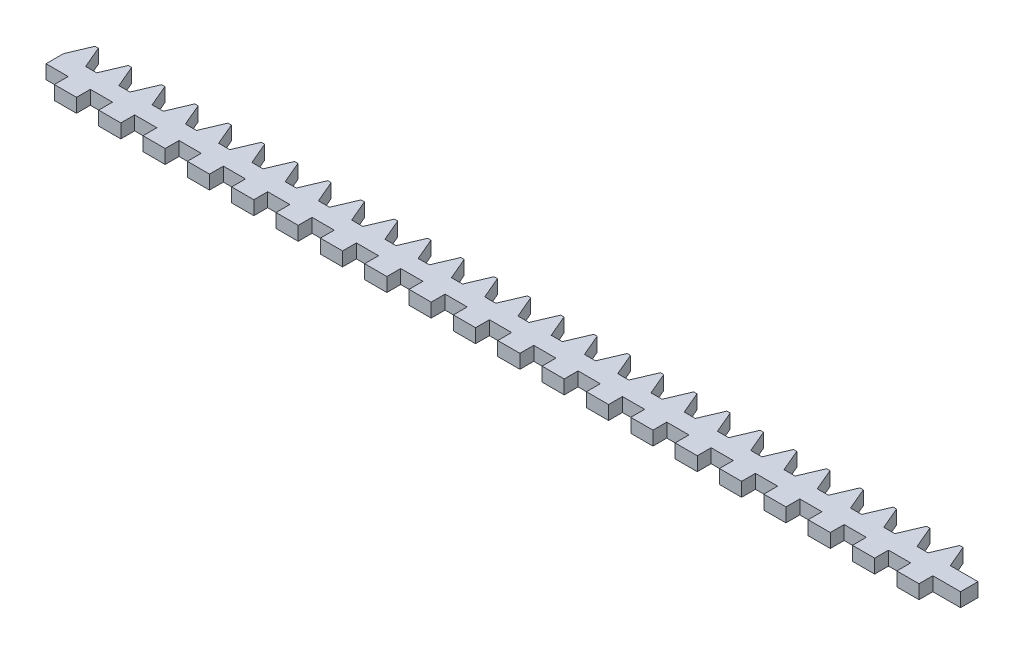
SolidWorks part; units mm, degrees
ref_plane "Front Plane" through (0, 0, 0) normal (0, 0, 1) x (1, 0, 0)
ref_plane "Top Plane" through (0, 0, 0) normal (0, 1, 0) x (1, 0, 0)
ref_plane "Right Plane" through (0, 0, 0) normal (1, 0, 0) x (0, 0, -1)
sketch "Sketch1" plane through (0, 0, 0) normal (0, 1, 0) x (1, 0, 0)
  line L0 (-139.4305, 2.0533) -> (-134.3505, 2.0533)
  line L1 (-134.3505, 6.0533) -> (-131.8105, 6.0533)
  line L2 (-139.4305, 6.0533) -> (-139.4305, 2.0533)
  line L3 (-134.3505, -1.1217) -> (-129.2705, -1.1217)
  line L4 (70.1195, 6.0533) -> (70.1195, 2.0533)
  line L5 (-129.2705, 2.0533) -> (-129.2705, -1.1217)
  line L6 (-134.3505, 2.0533) -> (-134.3505, -1.1217)
  line L7 (-129.2705, 2.0533) -> (-124.1905, 2.0533)
  line L8 (-124.1905, -1.1217) -> (-119.1105, -1.1217)
  line L9 (-119.1105, 2.0533) -> (-119.1105, -1.1217)
  line L10 (-124.1905, 2.0533) -> (-124.1905, -1.1217)
  line L11 (-119.1105, 2.0533) -> (-114.0305, 2.0533)
  line L12 (-114.0305, -1.1217) -> (-108.9505, -1.1217)
  line L13 (-108.9505, 2.0533) -> (-108.9505, -1.1217)
  line L14 (-114.0305, 2.0533) -> (-114.0305, -1.1217)
  line L15 (-108.9505, 2.0533) -> (-103.8705, 2.0533)
  line L16 (-103.8705, -1.1217) -> (-98.7905, -1.1217)
  line L17 (-98.7905, 2.0533) -> (-98.7905, -1.1217)
  line L18 (-103.8705, 2.0533) -> (-103.8705, -1.1217)
  line L19 (-98.7905, 2.0533) -> (-93.7105, 2.0533)
  line L20 (-93.7105, -1.1217) -> (-88.6305, -1.1217)
  line L21 (-88.6305, 2.0533) -> (-88.6305, -1.1217)
  line L22 (-93.7105, 2.0533) -> (-93.7105, -1.1217)
  line L23 (-88.6305, 2.0533) -> (-83.5505, 2.0533)
  line L24 (-83.5505, -1.1217) -> (-78.4705, -1.1217)
  line L25 (-78.4705, 2.0533) -> (-78.4705, -1.1217)
  line L26 (-83.5505, 2.0533) -> (-83.5505, -1.1217)
  line L27 (-78.4705, 2.0533) -> (-73.3905, 2.0533)
  line L28 (-73.3905, -1.1217) -> (-68.3105, -1.1217)
  line L29 (-68.3105, 2.0533) -> (-68.3105, -1.1217)
  line L30 (-73.3905, 2.0533) -> (-73.3905, -1.1217)
  line L31 (-68.3105, 2.0533) -> (-63.2305, 2.0533)
  line L32 (-63.2305, -1.1217) -> (-58.1505, -1.1217)
  line L33 (-58.1505, 2.0533) -> (-58.1505, -1.1217)
  line L34 (-63.2305, 2.0533) -> (-63.2305, -1.1217)
  line L35 (-58.1505, 2.0533) -> (-53.0705, 2.0533)
  line L36 (-53.0705, -1.1217) -> (-47.9905, -1.1217)
  line L37 (-47.9905, 2.0533) -> (-47.9905, -1.1217)
  line L38 (-53.0705, 2.0533) -> (-53.0705, -1.1217)
  line L39 (-47.9905, 2.0533) -> (-42.9105, 2.0533)
  line L40 (-42.9105, -1.1217) -> (-37.8305, -1.1217)
  line L41 (-37.8305, 2.0533) -> (-37.8305, -1.1217)
  line L42 (-42.9105, 2.0533) -> (-42.9105, -1.1217)
  line L43 (-37.8305, 2.0533) -> (-32.7505, 2.0533)
  line L44 (-32.7505, -1.1217) -> (-27.6705, -1.1217)
  line L45 (-27.6705, 2.0533) -> (-27.6705, -1.1217)
  line L46 (-32.7505, 2.0533) -> (-32.7505, -1.1217)
  line L47 (-27.6705, 2.0533) -> (-22.5905, 2.0533)
  line L48 (-22.5905, -1.1217) -> (-17.5105, -1.1217)
  line L49 (-17.5105, 2.0533) -> (-17.5105, -1.1217)
  line L50 (-22.5905, 2.0533) -> (-22.5905, -1.1217)
  line L51 (-17.5105, 2.0533) -> (-12.4305, 2.0533)
  line L52 (-12.4305, -1.1217) -> (-7.3505, -1.1217)
  line L53 (-7.3505, 2.0533) -> (-7.3505, -1.1217)
  line L54 (-12.4305, 2.0533) -> (-12.4305, -1.1217)
  line L55 (-7.3505, 2.0533) -> (-2.2705, 2.0533)
  line L56 (-2.2705, -1.1217) -> (2.8095, -1.1217)
  line L57 (2.8095, 2.0533) -> (2.8095, -1.1217)
  line L58 (-2.2705, 2.0533) -> (-2.2705, -1.1217)
  line L59 (2.8095, 2.0533) -> (7.8895, 2.0533)
  line L60 (7.8895, -1.1217) -> (12.9695, -1.1217)
  line L61 (12.9695, 2.0533) -> (12.9695, -1.1217)
  line L62 (7.8895, 2.0533) -> (7.8895, -1.1217)
  line L63 (12.9695, 2.0533) -> (18.0495, 2.0533)
  line L64 (18.0495, -1.1217) -> (23.1295, -1.1217)
  line L65 (23.1295, 2.0533) -> (23.1295, -1.1217)
  line L66 (18.0495, 2.0533) -> (18.0495, -1.1217)
  line L67 (23.1295, 2.0533) -> (28.2095, 2.0533)
  line L68 (28.2095, -1.1217) -> (33.2895, -1.1217)
  line L69 (33.2895, 2.0533) -> (33.2895, -1.1217)
  line L70 (28.2095, 2.0533) -> (28.2095, -1.1217)
  line L71 (33.2895, 2.0533) -> (38.3695, 2.0533)
  line L72 (38.3695, -1.1217) -> (43.4495, -1.1217)
  line L73 (43.4495, 2.0533) -> (43.4495, -1.1217)
  line L74 (38.3695, 2.0533) -> (38.3695, -1.1217)
  line L75 (43.4495, 2.0533) -> (48.5295, 2.0533)
  line L76 (48.5295, -1.1217) -> (53.6095, -1.1217)
  line L77 (53.6095, 2.0533) -> (53.6095, -1.1217)
  line L78 (48.5295, 2.0533) -> (48.5295, -1.1217)
  line L79 (53.6095, 2.0533) -> (58.6895, 2.0533)
  line L80 (58.6895, -1.1217) -> (63.7695, -1.1217)
  line L81 (63.7695, 2.0533) -> (63.7695, -1.1217)
  line L82 (58.6895, 2.0533) -> (58.6895, -1.1217)
  line L83 (-139.4305, 6.0533) -> (-139.4305, 32.7848) construction
  line L84 (63.7695, 2.0533) -> (70.1195, 2.0533)
  line L85 (-137.2715, 11.1333) -> (-136.5095, 11.1333)
  line L86 (-79.2398, 11.1333) -> (-137.2715, 11.1333) construction
  line L87 (-126.7305, 6.0533) -> (-124.1905, 6.0533)
  line L88 (-136.8905, 6.0609) -> (-136.8905, 13.7561) construction
  line L89 (-137.2715, 11.1333) -> (-159.3695, 11.1333) construction
  line L90 (-137.8109, 11.1333) -> (-137.2715, 11.1333) construction
  line L91 (-128.8895, 11.1333) -> (-126.7305, 6.0533)
  line L92 (-129.6515, 11.1333) -> (-128.8895, 11.1333)
  line L93 (-131.8105, 6.0533) -> (-129.6515, 11.1333)
  line L94 (-119.1105, 6.0533) -> (-116.5705, 6.0533)
  line L95 (-121.2695, 11.1333) -> (-119.1105, 6.0533)
  line L96 (-122.0315, 11.1333) -> (-121.2695, 11.1333)
  line L97 (-124.1905, 6.0533) -> (-122.0315, 11.1333)
  line L98 (-111.4905, 6.0533) -> (-108.9505, 6.0533)
  line L99 (-113.6495, 11.1333) -> (-111.4905, 6.0533)
  line L100 (-114.4115, 11.1333) -> (-113.6495, 11.1333)
  line L101 (-116.5705, 6.0533) -> (-114.4115, 11.1333)
  line L102 (-103.8705, 6.0533) -> (-101.3305, 6.0533)
  line L103 (-106.0295, 11.1333) -> (-103.8705, 6.0533)
  line L104 (-106.7915, 11.1333) -> (-106.0295, 11.1333)
  line L105 (-108.9505, 6.0533) -> (-106.7915, 11.1333)
  line L106 (-96.2505, 6.0533) -> (-93.7105, 6.0533)
  line L107 (-98.4095, 11.1333) -> (-96.2505, 6.0533)
  line L108 (-99.1715, 11.1333) -> (-98.4095, 11.1333)
  line L109 (-101.3305, 6.0533) -> (-99.1715, 11.1333)
  line L110 (-88.6305, 6.0533) -> (-86.0905, 6.0533)
  line L111 (-90.7895, 11.1333) -> (-88.6305, 6.0533)
  line L112 (-91.5515, 11.1333) -> (-90.7895, 11.1333)
  line L113 (-93.7105, 6.0533) -> (-91.5515, 11.1333)
  line L114 (-81.0105, 6.0533) -> (-78.4705, 6.0533)
  line L115 (-83.1695, 11.1333) -> (-81.0105, 6.0533)
  line L116 (-83.9315, 11.1333) -> (-83.1695, 11.1333)
  line L117 (-86.0905, 6.0533) -> (-83.9315, 11.1333)
  line L118 (-73.3905, 6.0533) -> (-70.8505, 6.0533)
  line L119 (-75.5495, 11.1333) -> (-73.3905, 6.0533)
  line L120 (-76.3115, 11.1333) -> (-75.5495, 11.1333)
  line L121 (-78.4705, 6.0533) -> (-76.3115, 11.1333)
  line L122 (-65.7705, 6.0533) -> (-63.2305, 6.0533)
  line L123 (-67.9295, 11.1333) -> (-65.7705, 6.0533)
  line L124 (-68.6915, 11.1333) -> (-67.9295, 11.1333)
  line L125 (-70.8505, 6.0533) -> (-68.6915, 11.1333)
  line L126 (-58.1505, 6.0533) -> (-55.6105, 6.0533)
  line L127 (-60.3095, 11.1333) -> (-58.1505, 6.0533)
  line L128 (-61.0715, 11.1333) -> (-60.3095, 11.1333)
  line L129 (-63.2305, 6.0533) -> (-61.0715, 11.1333)
  line L130 (-50.5305, 6.0533) -> (-47.9905, 6.0533)
  line L131 (-52.6895, 11.1333) -> (-50.5305, 6.0533)
  line L132 (-53.4515, 11.1333) -> (-52.6895, 11.1333)
  line L133 (-55.6105, 6.0533) -> (-53.4515, 11.1333)
  line L134 (-42.9105, 6.0533) -> (-40.3705, 6.0533)
  line L135 (-45.0695, 11.1333) -> (-42.9105, 6.0533)
  line L136 (-45.8315, 11.1333) -> (-45.0695, 11.1333)
  line L137 (-47.9905, 6.0533) -> (-45.8315, 11.1333)
  line L138 (-35.2905, 6.0533) -> (-32.7505, 6.0533)
  line L139 (-37.4495, 11.1333) -> (-35.2905, 6.0533)
  line L140 (-38.2115, 11.1333) -> (-37.4495, 11.1333)
  line L141 (-40.3705, 6.0533) -> (-38.2115, 11.1333)
  line L142 (-27.6705, 6.0533) -> (-25.1305, 6.0533)
  line L143 (-29.8295, 11.1333) -> (-27.6705, 6.0533)
  line L144 (-30.5915, 11.1333) -> (-29.8295, 11.1333)
  line L145 (-32.7505, 6.0533) -> (-30.5915, 11.1333)
  line L146 (-20.0505, 6.0533) -> (-17.5105, 6.0533)
  line L147 (-22.2095, 11.1333) -> (-20.0505, 6.0533)
  line L148 (-22.9715, 11.1333) -> (-22.2095, 11.1333)
  line L149 (-25.1305, 6.0533) -> (-22.9715, 11.1333)
  line L150 (-12.4305, 6.0533) -> (-9.8905, 6.0533)
  line L151 (-14.5895, 11.1333) -> (-12.4305, 6.0533)
  line L152 (-15.3515, 11.1333) -> (-14.5895, 11.1333)
  line L153 (-17.5105, 6.0533) -> (-15.3515, 11.1333)
  line L154 (-4.8105, 6.0533) -> (-2.2705, 6.0533)
  line L155 (-6.9695, 11.1333) -> (-4.8105, 6.0533)
  line L156 (-7.7315, 11.1333) -> (-6.9695, 11.1333)
  line L157 (-9.8905, 6.0533) -> (-7.7315, 11.1333)
  line L158 (2.8095, 6.0533) -> (5.3495, 6.0533)
  line L159 (0.6505, 11.1333) -> (2.8095, 6.0533)
  line L160 (-0.1115, 11.1333) -> (0.6505, 11.1333)
  line L161 (-2.2705, 6.0533) -> (-0.1115, 11.1333)
  line L162 (10.4295, 6.0533) -> (12.9695, 6.0533)
  line L163 (8.2705, 11.1333) -> (10.4295, 6.0533)
  line L164 (7.5085, 11.1333) -> (8.2705, 11.1333)
  line L165 (5.3495, 6.0533) -> (7.5085, 11.1333)
  line L166 (18.0495, 6.0533) -> (20.5895, 6.0533)
  line L167 (15.8905, 11.1333) -> (18.0495, 6.0533)
  line L168 (15.1285, 11.1333) -> (15.8905, 11.1333)
  line L169 (12.9695, 6.0533) -> (15.1285, 11.1333)
  line L170 (25.6695, 6.0533) -> (28.2095, 6.0533)
  line L171 (23.5105, 11.1333) -> (25.6695, 6.0533)
  line L172 (22.7485, 11.1333) -> (23.5105, 11.1333)
  line L173 (20.5895, 6.0533) -> (22.7485, 11.1333)
  line L174 (33.2895, 6.0533) -> (35.8295, 6.0533)
  line L175 (31.1305, 11.1333) -> (33.2895, 6.0533)
  line L176 (30.3685, 11.1333) -> (31.1305, 11.1333)
  line L177 (28.2095, 6.0533) -> (30.3685, 11.1333)
  line L178 (40.9095, 6.0533) -> (43.4495, 6.0533)
  line L179 (38.7505, 11.1333) -> (40.9095, 6.0533)
  line L180 (37.9885, 11.1333) -> (38.7505, 11.1333)
  line L181 (35.8295, 6.0533) -> (37.9885, 11.1333)
  line L182 (48.5295, 6.0533) -> (51.0695, 6.0533)
  line L183 (46.3705, 11.1333) -> (48.5295, 6.0533)
  line L184 (45.6085, 11.1333) -> (46.3705, 11.1333)
  line L185 (43.4495, 6.0533) -> (45.6085, 11.1333)
  line L186 (56.1495, 6.0533) -> (58.6895, 6.0533)
  line L187 (53.9905, 11.1333) -> (56.1495, 6.0533)
  line L188 (53.2285, 11.1333) -> (53.9905, 11.1333)
  line L189 (-137.2715, 11.1333) -> (-135.9701, 11.1333) construction
  line L190 (51.0695, 6.0533) -> (53.2285, 11.1333)
  line L191 (63.7695, 6.0533) -> (66.3095, 6.0533)
  line L192 (61.6105, 11.1333) -> (63.7695, 6.0533)
  line L193 (60.8485, 11.1333) -> (61.6105, 11.1333)
  line L194 (58.6895, 6.0533) -> (60.8485, 11.1333)
  line L195 (-134.3505, 6.0533) -> (-126.7305, 6.0533) construction
  line L196 (63.7695, 6.0533) -> (70.1195, 6.0533)
  line L197 (-139.4305, 6.0533) -> (-137.2715, 11.1333)
  line L198 (-136.5095, 11.1333) -> (-134.3505, 6.0533)
  line L216 (-137.2715, 11.1333) -> (-136.5095, 11.1333) construction
  point P60 (-136.8905, 11.1333)
  point P226 (-136.8905, 11.1333)
  dimension "D1" = 209.55
  dimension "D2" = 4
  dimension "D3" = 5.08
  dimension "D4" = 10.16
  dimension "D5" = 3.175
  dimension "D6" = 5.08
  dimension "D7" = 2.54
  dimension "D8" = 1.6196
  dimension "D9" = 0.381
  dimension "D10" = 0.5394
  dimension "D11" = 7.62
extrude "Boss-Extrude1" add sketch "Sketch1" along normal blind 3.175
sketch "Sketch2" plane through (0, 0, 0) normal (0, -1, 0) x (1, 0, 0)
sketch "Sketch3" plane through (0, 0, 0) normal (0, 0, 1) x (1, 0, 0)
